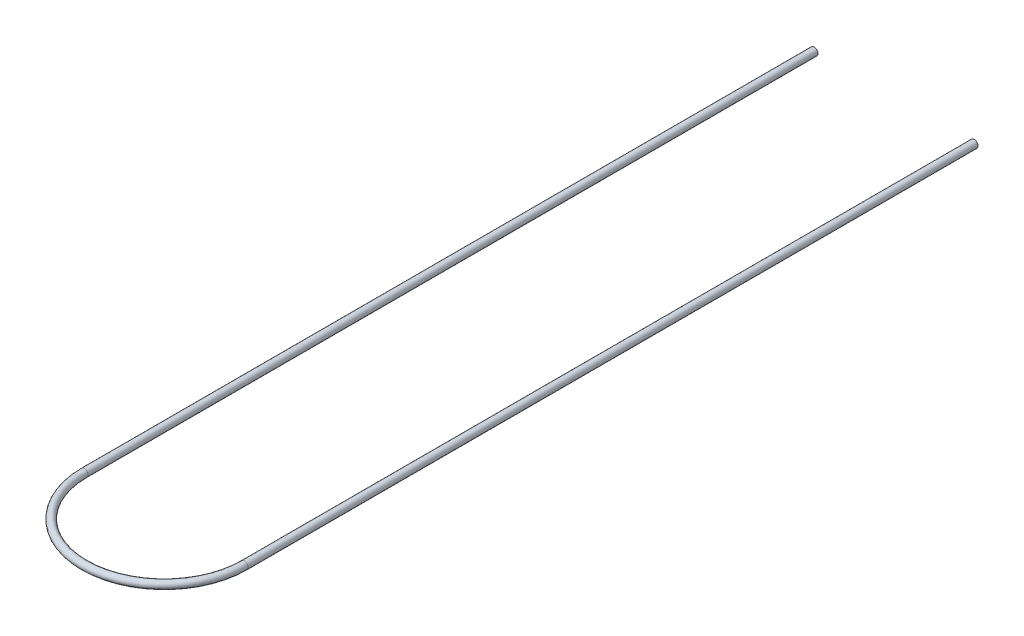
SolidWorks part; units mm, degrees
ref_plane "Front Plane" through (0, 0, 0) normal (0, 0, 1) x (1, 0, 0)
ref_plane "Top Plane" through (0, 0, 0) normal (0, 1, 0) x (1, 0, 0)
ref_plane "Right Plane" through (0, 0, 0) normal (1, 0, 0) x (0, 0, -1)
sketch "Sketch1" plane through (0, 0, 0) normal (0, 1, 0) x (1, 0, 0)
  line L0 (429.23, -300) -> (429.23, -2440)
  line L2 (-40, -300) -> (-40, -2440)
  arc A0 (-40, -2440) -> (429.23, -2440) centre (194.615, -2440) ccw
  dimension "D1" = 2140
  dimension "D2" = 469.23
ref_plane "Plane1" through (429.23, 0, 300) normal (0, 0, -1) x (-1, 0, 0)
sketch "Sketch2" plane through (429.23, 0, 300) normal (0, 0, -1) x (-1, 0, 0)
  circle A0 centre (0, 0) radius 9.95
  circle A1 centre (0, 0) radius 11.1
  dimension "D1" = 22.2
  dimension "D2" = 19.9
sweep "Sweep1" add profiles "Sketch2" path "Sketch1"
